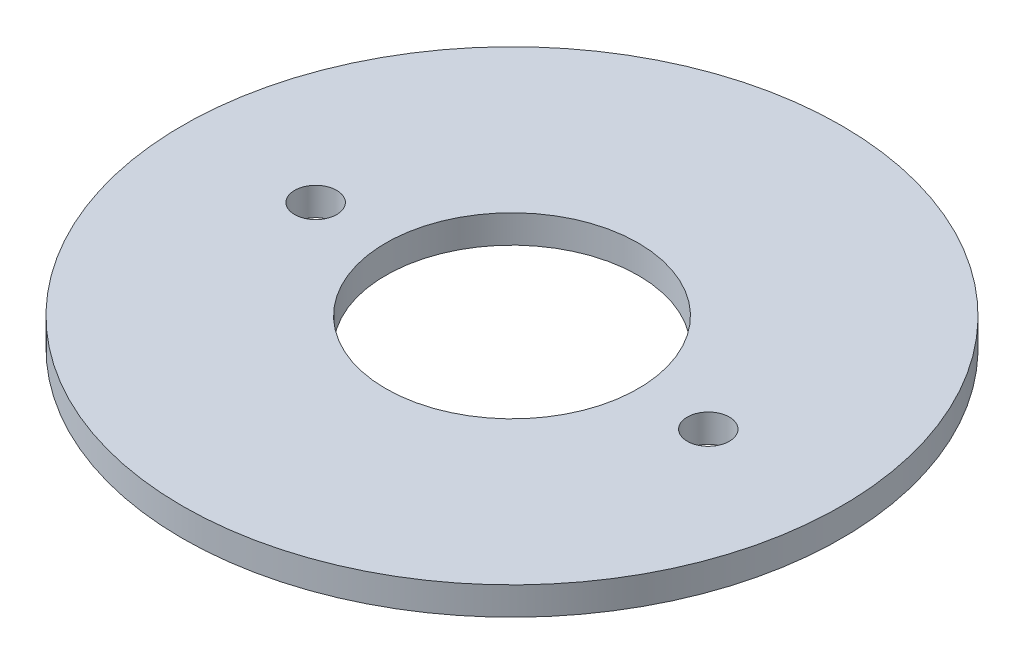
SolidWorks part; units mm, degrees
material "PVC Rigid"
ref_plane "Front Plane" through (0, 0, 0) normal (0, 0, 1) x (1, 0, 0)
ref_plane "Top Plane" through (0, 0, 0) normal (0, 1, 0) x (1, 0, 0)
ref_plane "Right Plane" through (0, 0, 0) normal (1, 0, 0) x (0, 0, -1)
sketch "Sketch2" plane through (0, 0, 0) normal (0, 1, 0) x (1, 0, 0)
  line L0 (-46.1437, 0) -> (54.1251, 0) construction
  line L1 (0, 43.8239) -> (0, -49.8219) construction
  circle A0 centre (0, 0) radius 23.5
  circle A1 centre (0, 0) radius 9
  circle A3 centre (-14, 0) radius 1.5
  circle A4 centre (14, 0) radius 1.5
  dimension "D1" = 47
  dimension "D2" = 18
  dimension "D3" = 3
  dimension "D4" = 14
extrude "Boss-Extrude1" add sketch "Sketch2" along normal blind 2
